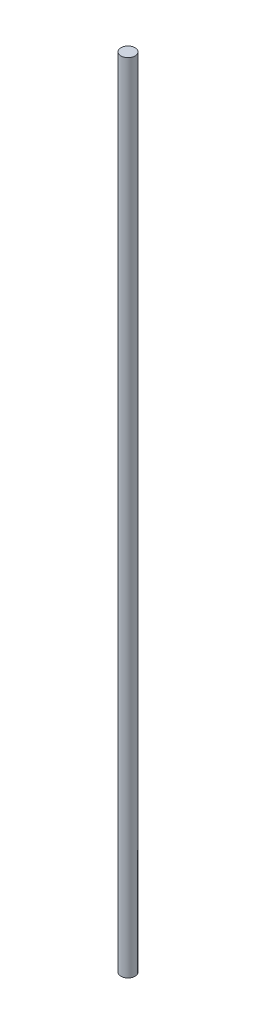
SolidWorks part; units mm, degrees
ref_plane "Front Plane" through (0, 0, 0) normal (0, 0, 1) x (1, 0, 0)
ref_plane "Top Plane" through (0, 0, 0) normal (0, 1, 0) x (1, 0, 0)
ref_plane "Right Plane" through (0, 0, 0) normal (1, 0, 0) x (0, 0, -1)
sketch "Sketch1" plane through (0, 0, 0) normal (0, 1, 0) x (1, 0, 0)
  circle A0 centre (0, 0) radius 3.175
extrude "Boss-Extrude1" add sketch "Sketch1" along normal blind 355.6
